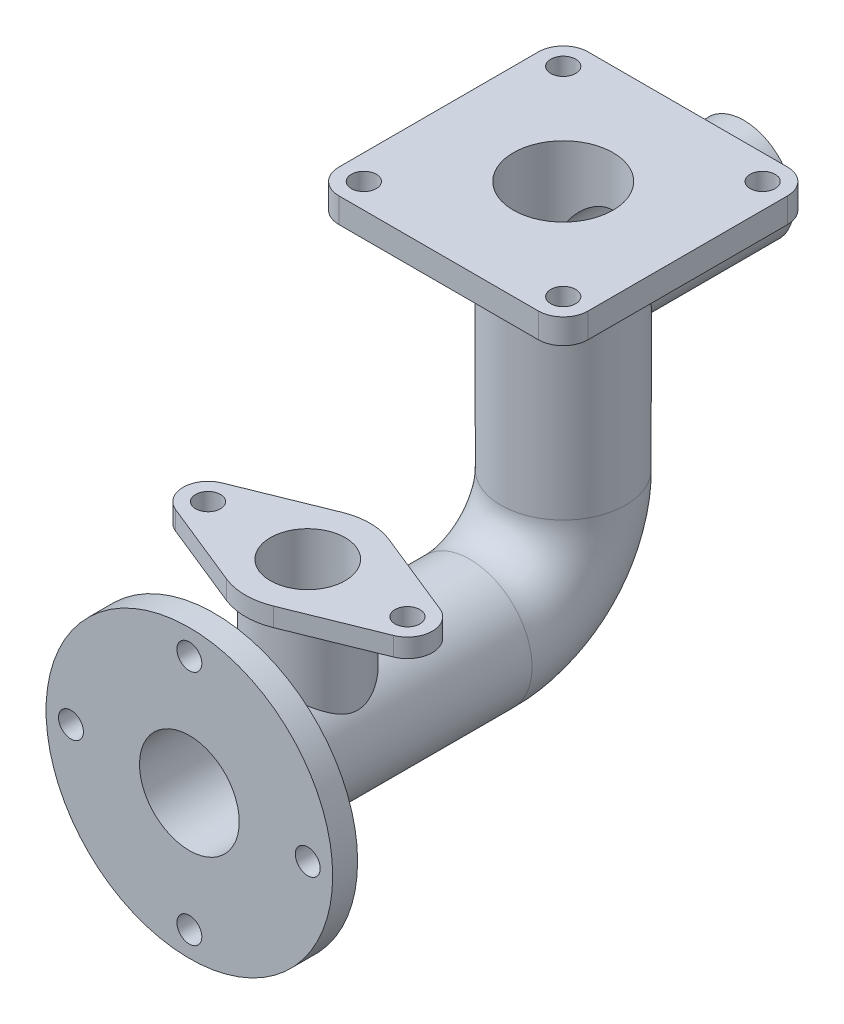
SolidWorks part; units mm, degrees
ref_plane "Front Plane" through (0, 0, 0) normal (0, 0, 1) x (1, 0, 0)
ref_plane "Top Plane" through (0, 0, 0) normal (0, 1, 0) x (1, 0, 0)
ref_plane "Right Plane" through (0, 0, 0) normal (1, 0, 0) x (0, 0, -1)
sketch "Sketch1" plane through (0, 0, 0) normal (1, 0, 0) x (0, 0, -1)
  line L0 (0, 0) -> (56.25, 0)
  line L1 (75, 18.75) -> (75, 68.75)
  arc A0 (56.25, 0) -> (75, 18.75) centre (56.25, 18.75) ccw
  dimension "D2" = 18.75
  dimension "D1" = 56.25
  dimension "D3" = 50
sketch "Sketch2" plane through (0, 0, 0) normal (0, 0, 1) x (1, 0, 0)
  circle A0 centre (0, 0) radius 10
  circle A1 centre (0, 0) radius 12.5
  dimension "D1" = 20
  dimension "D2" = 25
sweep "Sweep1" add profiles "Sketch2" path "Sketch1"
sketch "Sketch3" plane through (0, 0, 0) normal (0, 0, 1) x (1, 0, 0)
  circle A0 centre (0, 0) radius 28.75
  circle A1 centre (0, 0) radius 10 construction
  circle A2 centre (0, 0) radius 10
  dimension "D1" = 57.5
extrude "Boss-Extrude1" add sketch "Sketch3" against normal blind 5
hole_wizard "Hole1" positions "Sketch4" profile "Sketch5" legacy
sketch "Sketch4" plane through (0, 0, 0) normal (0, 0, 1) x (1, 0, 0)
  point P0 (23.75, 0)
  point P4 (0, 0)
  dimension "D1" = 23.75
sketch "Sketch5" plane through (23.75, 0, 0) normal (1, 0, 0) x (0, -1, 0)
  line L0 (0, 0) -> (0, 5)
  line L1 (0, 5) -> (2.5, 5)
  line L2 (2.5, 5) -> (2.5, 0)
  line L3 (2.5, 0) -> (0, 0)
  line L4 (0, 110) -> (0, -10) construction
  dimension "Diameter" = 5
  dimension "Depth" = 5
pattern_circular "CirPattern1" count 4 over 360 about axis through (0, 0, 0) along (0, 0, 1) of "Hole1"
sketch "Sketch6" plane through (0, 68.75, 0) normal (0, 1, 0) x (1, 0, 0)
  line L0 (0, 75) -> (0, 116.6283) construction
  line L2 (-25, 100) -> (25, 100)
  line L3 (-25, 100) -> (-25, 50)
  line L4 (-25, 50) -> (25, 50)
  line L5 (25, 100) -> (25, 50)
  line L6 (-25, 100) -> (25, 50) construction
  line L7 (-25, 50) -> (25, 100) construction
  circle A0 centre (0, 75) radius 10 construction
  circle A1 centre (0, 75) radius 10
  dimension "D1" = 50
  dimension "D2" = 50
extrude "Boss-Extrude2" add sketch "Sketch6" against normal blind 5
fillet "Fillet1" radius 5 4 edges at (-25, 66.25, -100) (25, 66.25, -100) (25, 66.25, -50) (-25, 66.25, -50)
hole_wizard "Hole2" positions "Sketch7" profile "Sketch8" legacy end condition up to next
sketch "Sketch7" plane through (0, 68.75, 0) normal (0, 1, 0) x (1, 0, 0)
  point P0 (-20, 55)
  point P3 (20, 55)
  point P6 (20, 95)
  point P9 (-20, 95)
sketch "Sketch8" plane through (-20, 68.75, -55) normal (1, 0, 0) x (0, 0, 1)
  line L0 (0, 0) -> (0, 5)
  line L1 (0, 5) -> (2.5, 5)
  line L2 (2.5, 5) -> (2.5, 0)
  line L3 (2.5, 0) -> (0, 0)
  line L4 (0, 110) -> (0, -10) construction
  dimension "Diameter" = 5
  dimension "Depth" = 5
ref_plane "Plane1" through (0, 28.75, 0) normal (0, 1, 0) x (1, 0, 0)
sketch "Sketch9" plane through (0, 28.75, 0) normal (0, 1, 0) x (1, 0, 0)
  line L0 (-28.75, 0) -> (28.75, 0) construction
  line L1 (0, 75) -> (0, 23.75) construction
  circle A0 centre (0, 23.75) radius 10
  dimension "D1" = 20
  dimension "D4" = 23.75
extrude "Boss-Extrude3" add sketch "Sketch9" against normal up to next
hole_wizard "Hole3" positions "Sketch11" profile "Sketch12" legacy
sketch "Sketch11" plane through (0, 28.75, 0) normal (0, 1, 0) x (1, 0, 0)
  point P0 (0, 23.75)
sketch "Sketch12" plane through (0, 28.75, -23.75) normal (1, 0, 0) x (0, 0, 1)
  line L0 (0, 0) -> (0, 18.75)
  line L1 (0, 18.75) -> (7.5, 18.75)
  line L2 (7.5, 18.75) -> (7.5, 0)
  line L3 (7.5, 0) -> (0, 0)
  line L4 (0, 110) -> (0, -10) construction
  dimension "Diameter" = 15
  dimension "Depth" = 18.75
sketch "Sketch13" plane through (0, 28.75, 0) normal (0, 1, 0) x (1, 0, 0)
  line L0 (0, 0) -> (0, 61.2681) construction
  line L1 (-21.875, 28.3851) -> (-4.6875, 35.3378)
  line L2 (-21.875, 19.1149) -> (-4.6875, 12.1622)
  line L3 (21.875, 28.3851) -> (4.6875, 35.3378)
  line L4 (21.875, 19.1149) -> (4.6875, 12.1622)
  arc A0 (4.6875, 35.3378) -> (-4.6875, 35.3378) centre (0, 23.75) ccw
  arc A1 (21.875, 19.1149) -> (21.875, 28.3851) centre (20, 23.75) ccw
  arc A2 (-21.875, 19.1149) -> (-21.875, 28.3851) centre (-20, 23.75) cw
  circle A3 centre (0, 23.75) radius 7.5 construction
  circle A4 centre (0, 23.75) radius 7.5
  arc A5 (-4.6875, 12.1622) -> (4.6875, 12.1622) centre (0, 23.75) ccw
  circle A6 centre (-20, 23.75) radius 2.5
  circle A7 centre (20, 23.75) radius 2.5
  dimension "D1" = 25
  dimension "D2" = 10
  dimension "D4" = 5
  dimension "D3" = 40
extrude "Boss-Extrude4" add sketch "Sketch13" against normal blind 3.75
ref_plane "Plane2" through (0, 0, -111.25) normal (0, 0, 1) x (1, 0, 0)
sketch "Sketch14" plane through (0, 0, -111.25) normal (0, 0, 1) x (1, 0, 0)
  line L0 (20, 68.75) -> (-20, 68.75) construction
  circle A0 centre (0, 51.25) radius 10
  dimension "D1" = 20
  dimension "D2" = 17.5
extrude "Boss-Extrude5" add sketch "Sketch14" along normal up to next
hole_wizard "Hole4" positions "Sketch15" profile "Sketch16" legacy
sketch "Sketch15" plane through (0, 0, -111.25) normal (0, 0, -1) x (-1, 0, 0)
  point P0 (0, 51.25)
sketch "Sketch16" plane through (0, 51.25, -111.25) normal (1, 0, 0) x (0, 1, 0)
  line L0 (0, 0) -> (0, 26.25)
  line L1 (0, 26.25) -> (7.5, 26.25)
  line L2 (7.5, 26.25) -> (7.5, 0)
  line L3 (7.5, 0) -> (0, 0)
  line L4 (0, 110) -> (0, -10) construction
  dimension "Diameter" = 15
  dimension "Depth" = 26.25
